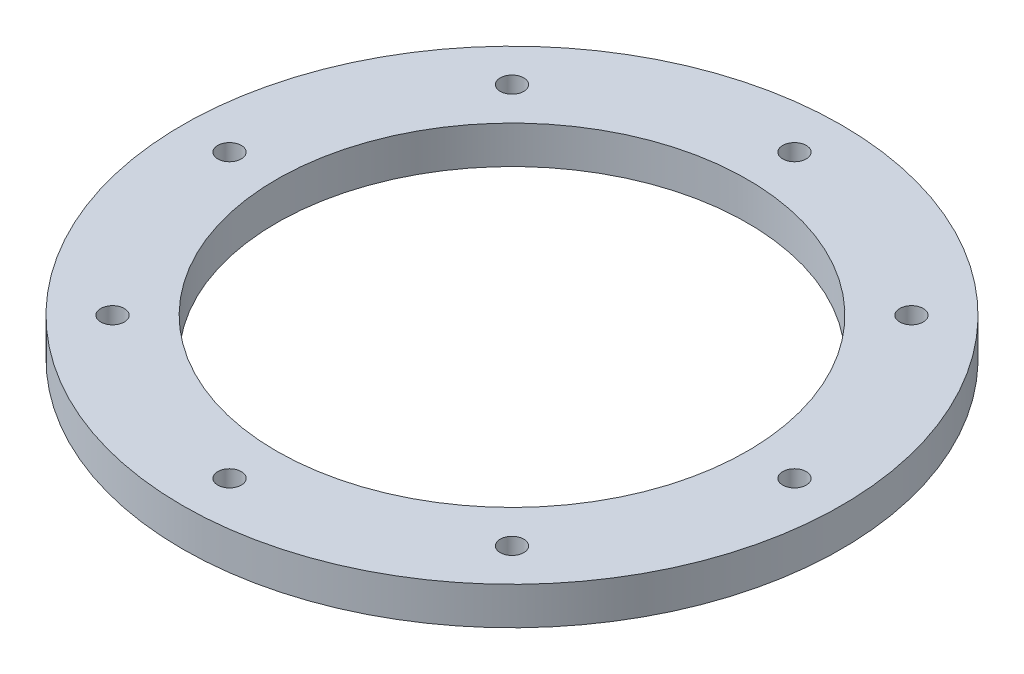
SolidWorks part; units mm, degrees
ref_plane "Front Plane" through (0, 0, 0) normal (0, 0, 1) x (1, 0, 0)
ref_plane "Top Plane" through (0, 0, 0) normal (0, 1, 0) x (1, 0, 0)
ref_plane "Right Plane" through (0, 0, 0) normal (1, 0, 0) x (0, 0, -1)
sketch "Sketch1" plane through (0, 0, 0) normal (0, 1, 0) x (1, 0, 0)
  circle A0 centre (0, 0) radius 25
  circle A1 centre (0, 0) radius 35
  circle A14 centre (0, 30) radius 1.25
  circle A15 centre (21.2132, 21.2132) radius 1.25
  circle A16 centre (30, 0) radius 1.25
  circle A17 centre (-21.2132, 21.2132) radius 1.25
  circle A18 centre (-30, 0) radius 1.25
  circle A19 centre (-21.2132, -21.2132) radius 1.25
  circle A20 centre (0, -30) radius 1.25
  circle A21 centre (21.2132, -21.2132) radius 1.25
  dimension "D1" = 50
  dimension "D2" = 70
  dimension "D5" = 2.5
  dimension "D21" = 2.5
  dimension "D22" = 2.5
  dimension "D23" = 2.5
  dimension "D24" = 2.5
  dimension "D25" = 2.5
  dimension "D26" = 2.5
  dimension "D10" = 2.5
extrude "Boss-Extrude1" add sketch "Sketch1" along normal blind 4
